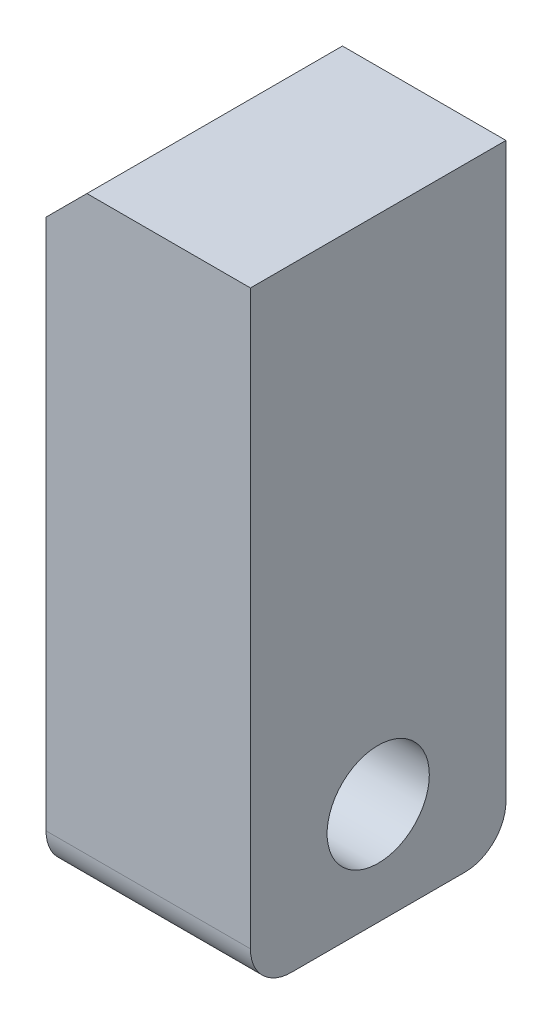
SolidWorks part; units mm, degrees
ref_plane "Front" through (0, 0, 0) normal (0, 0, 1) x (1, 0, 0)
ref_plane "Top" through (0, 0, 0) normal (0, 1, 0) x (1, 0, 0)
ref_plane "Right" through (0, 0, 0) normal (1, 0, 0) x (0, 0, -1)
sketch "草图1" plane through (0, 0, 0) normal (1, 0, 0) x (0, 0, -1)
  line L1 (6.25, -15) -> (-6.25, -15)
  line L2 (6.25, -15) -> (6.25, 15)
  line L3 (6.25, 15) -> (-6.25, 15)
  line L4 (-6.25, -15) -> (-6.25, 15)
  line L5 (6.25, -15) -> (-6.25, 15) construction
  line L6 (6.25, 15) -> (-6.25, -15) construction
  point P0 (0, 0)
  dimension "D1" = 12.5
  dimension "D2" = 30
extrude "凸台-拉伸1" add sketch "草图1" along normal blind 10
sketch "草图2" plane through (10, 0, 0) normal (1, 0, 0) x (0, 0, -1)
  line L0 (0, -15) -> (0, 15) construction
  line L1 (-6.25, -15) -> (6.25, -15) construction
  line L2 (6.25, 15) -> (-6.25, 15) construction
  circle A0 centre (0, -10) radius 2.5
  dimension "D1" = 5
  dimension "D2" = 5
extrude "切除-拉伸1" cut sketch "草图2" against normal through all and the other way through all
fillet "圆角1" radius 2 2 edges at (5, -15, 6.25) (5, -15, -6.25)
chamfer "倒角1" distance 2 angle 45 1 edges at (0, 15, 0)
